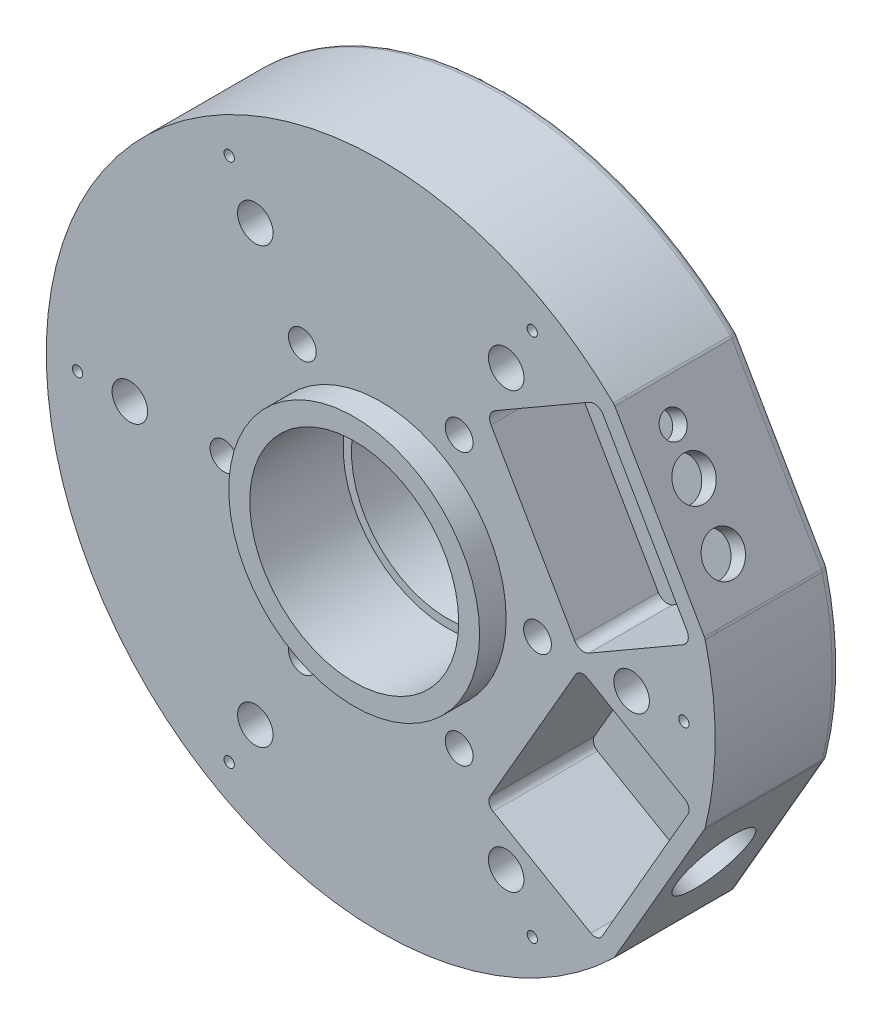
SolidWorks part; units mm, degrees
ref_plane "Front Plane" through (0, 0, 0) normal (0, 0, 1) x (1, 0, 0)
ref_plane "Top Plane" through (0, 0, 0) normal (0, 1, 0) x (1, 0, 0)
ref_plane "Right Plane" through (0, 0, 0) normal (1, 0, 0) x (0, 0, -1)
ref_plane "Plane1" through (0, 0, 30) normal (0, 0, 1) x (1, 0, 0)
sketch "Sketch1" plane through (0, 0, 30) normal (0, 0, 1) x (1, 0, 0)
  line L0 (77.5352, 19.7051) -> (55.8327, 57.2949)
  line L1 (55.8327, -57.2949) -> (77.5352, -19.7051)
  arc A0 (55.8327, 57.2949) -> (55.8327, -57.2949) centre (0, 0) ccw
  arc A1 (77.5352, -19.7051) -> (77.5352, 19.7051) centre (0, 0) ccw
extrude "Boss-Extrude1" add sketch "Sketch1" against normal blind 30
sketch "Sketch2" plane through (0, 0, 30) normal (0, 0, 1) x (1, 0, 0)
  line L0 (77.3961, -19.946) -> (77.5352, -19.7051)
  arc A0 (77.5352, -19.7051) -> (77.6042, -19.4318) centre (0, 0) ccw
  arc A1 (77.6042, -19.4318) -> (77.3961, -19.946) centre (75.664, -18.946) cw
extrude "Cut-Extrude1" cut sketch "Sketch2" against normal blind 2.8
sketch "Sketch3" plane through (0, 0, 30) normal (0, 0, 1) x (1, 0, 0)
  line L0 (55.9718, 57.054) -> (55.8327, 57.2949)
  arc A0 (55.8327, 57.2949) -> (55.6305, 57.4913) centre (0, 0) ccw
  arc A1 (55.6305, 57.4913) -> (55.9718, 57.054) centre (54.2398, 56.054) cw
extrude "Cut-Extrude2" cut sketch "Sketch3" against normal blind 2.8
sketch "Sketch4" plane through (0, 0, 30) normal (0, 0, 1) x (1, 0, 0)
  line L0 (55.8327, -57.2949) -> (55.9718, -57.054)
  arc A0 (55.9718, -57.054) -> (55.6305, -57.4913) centre (54.2398, -56.054) cw
  arc A1 (55.6305, -57.4913) -> (55.8327, -57.2949) centre (0, 0) ccw
extrude "Cut-Extrude3" cut sketch "Sketch4" against normal blind 2.8
sketch "Sketch5" plane through (0, 0, 30) normal (0, 0, 1) x (1, 0, 0)
  line L0 (77.5352, 19.7051) -> (77.3961, 19.946)
  arc A0 (77.3961, 19.946) -> (77.6042, 19.4318) centre (75.664, 18.946) cw
  arc A1 (77.6042, 19.4318) -> (77.5352, 19.7051) centre (0, 0) ccw
extrude "Cut-Extrude4" cut sketch "Sketch5" against normal blind 2.8
sketch "Sketch6" plane through (0, 0, 30) normal (0, 0, 1) x (1, 0, 0)
  line L0 (51.9699, -55.9856) -> (74.4699, -17.0144)
  line L1 (74.4699, -17.0144) -> (47.6231, -1.5144)
  line L2 (47.6231, -1.5144) -> (25.1231, -40.4856)
  line L3 (25.1231, -40.4856) -> (51.9699, -55.9856)
extrude "Cut-Extrude5" cut sketch "Sketch6" against normal blind 25
sketch "Sketch7" plane through (0, 0, 30) normal (0, 0, 1) x (1, 0, 0)
  line L0 (51.9699, 55.9856) -> (25.1231, 40.4856)
  line L1 (25.1231, 40.4856) -> (47.6231, 1.5144)
  line L2 (47.6231, 1.5144) -> (74.4699, 17.0144)
  line L3 (74.4699, 17.0144) -> (51.9699, 55.9856)
extrude "Cut-Extrude6" cut sketch "Sketch7" against normal blind 20
hole_wizard "CBORE for M8 Hex Head Bolt1" positions "Sketch9" profile "Sketch8" counterbore size "M8" standard "ANSI Metric"
sketch "Sketch9" plane through (0, 0, 0) normal (0, 0, -1) x (-1, 0, 0)
  point P0 (30, -51.9615)
  point P1 (-30, -51.9615)
  point P2 (-60, 0)
  point P3 (-30, 51.9615)
  point P4 (30, 51.9615)
  point P5 (60, 0)
sketch "Sketch8" plane through (-30, -51.9615, 0) normal (1, 0, 0) x (0, 1, 0)
  line L0 (0, 0) -> (0, 30)
  line L1 (0, 30) -> (4.25, 30)
  line L3 (4.25, 30) -> (4.25, 9)
  line L4 (4.25, 9) -> (7, 9)
  line L5 (7, 9) -> (7, 0)
  line L7 (7, 0) -> (0, 0)
  line L11 (0, -6.35) -> (0, 107.95) construction
  dimension "Thru Hole Dia." = 8.5
  dimension "Thru Hole Depth" = 30
  dimension "C'Bore Dia." = 14
  dimension "C'Bore Depth" = 9
hole_wizard "CBORE for M42 Hex Head Bolt1" positions "Sketch11" profile "Sketch10" counterbore size "M42" standard "ANSI Metric"
sketch "Sketch11" plane through (0, 0, 30) normal (0, 0, 1) x (1, 0, 0)
  point P0 (0, 0)
sketch "Sketch10" plane through (0, 0, 30) normal (1, 0, 0) x (0, -1, 0)
  line L0 (0, 0) -> (0, 30)
  line L1 (0, 30) -> (23, 30)
  line L3 (23, 30) -> (23, 16)
  line L4 (23, 16) -> (30, 16)
  line L5 (30, 16) -> (30, 0)
  line L7 (30, 0) -> (0, 0)
  line L11 (0, -6.35) -> (0, 107.95) construction
  dimension "Thru Hole Dia." = 46
  dimension "Thru Hole Depth" = 30
  dimension "C'Bore Dia." = 60
  dimension "C'Bore Depth" = 16
hole_wizard "M6 Clearance Hole1" positions "Sketch15" profile "Sketch14" hole size "M6" standard "ANSI Metric"
sketch "Sketch15" plane through (0, 0, 0) normal (0, 0, -1) x (-1, 0, 0)
  point P0 (18.75, 32.476)
  point P1 (-18.75, 32.476)
  point P2 (-37.5, 0)
  point P3 (-18.75, -32.476)
  point P4 (18.75, -32.476)
  point P5 (37.5, 0)
sketch "Sketch14" plane through (-18.75, 32.476, 0) normal (1, 0, 0) x (0, 1, 0)
  line L0 (0, 0) -> (0, 30)
  line L1 (0, 30) -> (3.3235, 30)
  line L2 (3.3235, 30) -> (3.3235, 0)
  line L5 (3.3235, 0) -> (0, 0)
  line L11 (0, -6.35) -> (0, 107.95) construction
  dimension "Thru Hole Dia." = 6.647
  dimension "Thru Hole Depth" = 30
hole_wizard "Ø18.0 (18) Diameter Hole1" positions "Sketch17" profile "Sketch16" hole size "Ø18.0" standard "ANSI Metric"
sketch "Sketch17" plane through (66.684, -38.5, 0) normal (0.866, -0.5, 0) x (0, 0, -1)
  point P0 (-17, 0)
sketch "Sketch16" plane through (66.684, -38.5, 17) normal (0, 0, 1) x (0.5, 0.866, 0)
  line L0 (0, 0) -> (0, 4)
  line L1 (0, 4) -> (9, 4)
  line L2 (9, 4) -> (9, 0)
  line L5 (9, 0) -> (0, 0)
  line L11 (0, -6.35) -> (0, 107.95) construction
  dimension "Thru Hole Dia." = 18
  dimension "Thru Hole Depth" = 4
hole_wizard "Ø6.0 (6) Diameter Hole1" positions "Sketch19" profile "Sketch18" hole size "Ø6.0" standard "ANSI Metric"
sketch "Sketch19" plane through (66.684, 38.5, 0) normal (0.866, 0.5, 0) x (0, 0, -1)
  point P0 (-20, 13.5)
sketch "Sketch18" plane through (59.934, 50.1913, 20) normal (0, 0, 1) x (-0.5, 0.866, 0)
  line L0 (0, 0) -> (0, 4)
  line L1 (0, 4) -> (3, 4)
  line L2 (3, 4) -> (3, 0)
  line L5 (3, 0) -> (0, 0)
  line L11 (0, -6.35) -> (0, 107.95) construction
  dimension "Thru Hole Dia." = 6
  dimension "Thru Hole Depth" = 4
hole_wizard "Ø9.5 (9.5) Diameter Hole1" positions "Sketch21" profile "Sketch20" hole size "Ø9.5" standard "ANSI Metric"
sketch "Sketch21" plane through (66.684, 38.5, 0) normal (0.866, 0.5, 0) x (0, 0, -1)
  point P0 (-20, 3.5)
  point P1 (-20, -10.5)
sketch "Sketch20" plane through (64.934, 41.5311, 20) normal (0, 0, 1) x (-0.5, 0.866, 0)
  line L0 (0, 0) -> (0, 4)
  line L1 (0, 4) -> (4.75, 4)
  line L2 (4.75, 4) -> (4.75, 0)
  line L5 (4.75, 0) -> (0, 0)
  line L11 (0, -6.35) -> (0, 107.95) construction
  dimension "Thru Hole Dia." = 9.5
  dimension "Thru Hole Depth" = 4
hole_wizard "M2 Clearance Hole1" positions "Sketch23" profile "Sketch22" hole size "M2" standard "ANSI Metric"
sketch "Sketch23" plane through (0, 0, 30) normal (0, 0, 1) x (1, 0, 0)
  point P0 (-36.25, -62.7868)
  point P1 (-72.5, 0)
  point P2 (-36.25, 62.7868)
  point P3 (36.25, 62.7868)
  point P4 (72.5, 0)
  point P5 (36.25, -62.7868)
sketch "Sketch22" plane through (-36.25, -62.7868, 30) normal (1, 0, 0) x (0, -1, 0)
  line L0 (0, 0) -> (0, 12.7388)
  line L1 (0, 12.7388) -> (1.2295, 12)
  line L2 (1.2295, 12) -> (1.2295, 0)
  line L5 (1.2295, 0) -> (0, 0)
  line L10 (0, 12.7388) -> (-1.2295, 12) construction
  line L11 (0, -6.35) -> (0, 107.95) construction
  dimension "Hole Dia." = 2.459
  dimension "Hole Depth" = 12
  dimension "Drill Angle" = 118
fillet "Fillet1" radius 2 12 edges at (25.1231, -40.4856, 17.5) (74.4699, -17.0144, 17.5) (77.5352, -19.7051, 13.6) (80, 0, 0) (77.5352, 19.7051, 13.6) (55.8327, -57.2949, 13.6) (55.8327, 57.2949, 13.6) (66.684, -38.5, 0) (66.684, 38.5, 0) (-80, 0, 0) (51.9699, -55.9856, 17.5) (47.6231, -1.5144, 17.5)
fillet "Fillet2" radius 2.5 4 edges at (47.6231, 1.5144, 20) (74.4699, 17.0144, 20) (51.9699, 55.9856, 20) (25.1231, 40.4856, 20)
sketch "Sketch24" plane through (0, 0, 14) normal (0, 0, 1) x (1, 0, 0)
  circle A0 centre (0, 0) radius 25
  circle A2 centre (0, 0) radius 30
  dimension "D1" = 60
  dimension "D2" = 50
extrude "Boss-Extrude2" add sketch "Sketch24" along normal offset from surface (22.35 mm away) 6.35 up to face at (-35.0205, -62.7868, 30) offset beyond the face yes
